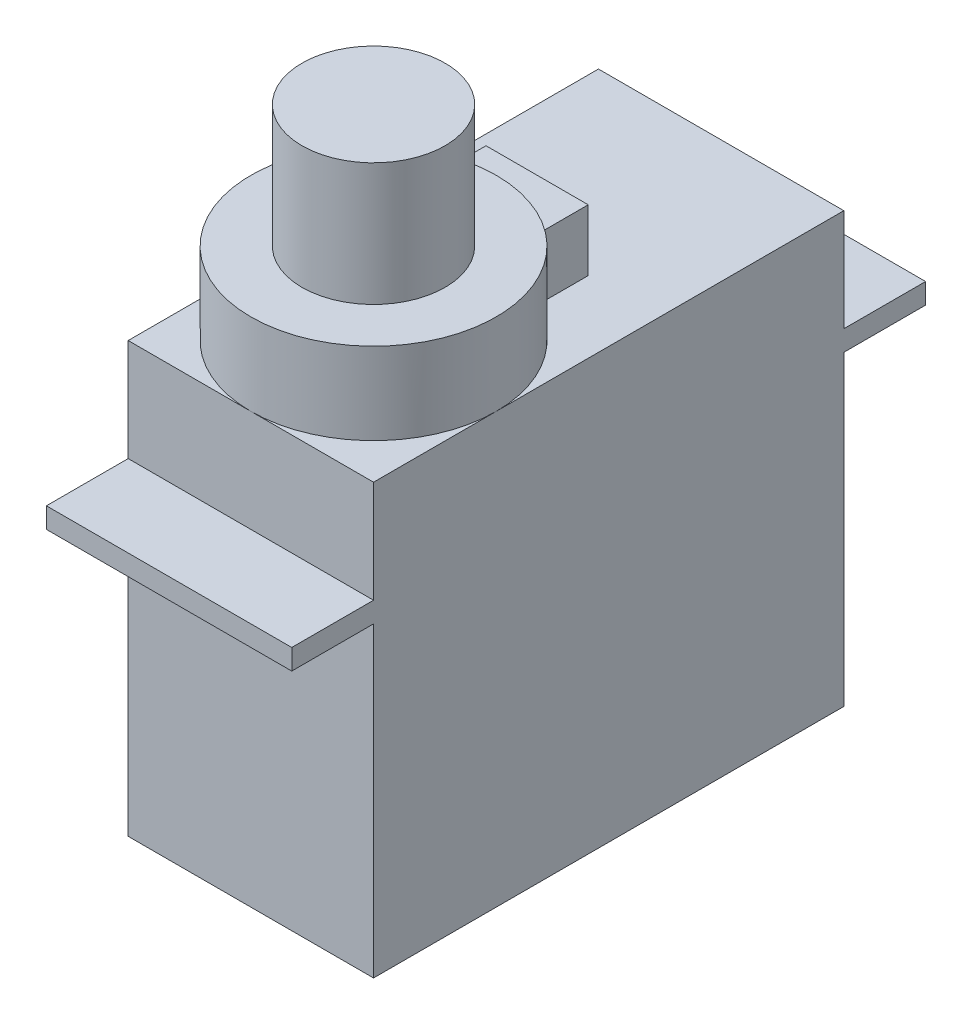
SolidWorks part; units mm, degrees
ref_plane "Front Plane" through (0, 0, 0) normal (0, 0, 1) x (1, 0, 0)
ref_plane "Top Plane" through (0, 0, 0) normal (0, 1, 0) x (1, 0, 0)
ref_plane "Right Plane" through (0, 0, 0) normal (1, 0, 0) x (0, 0, -1)
sketch "Sketch1" plane through (0, 0, 0) normal (0, 1, 0) x (1, 0, 0)
  line L1 (-6, -11.5) -> (6, -11.5)
  line L2 (-6, -11.5) -> (-6, 11.5)
  line L3 (-6, 11.5) -> (6, 11.5)
  line L4 (6, -11.5) -> (6, 11.5)
  line L5 (-6, -11.5) -> (6, 11.5) construction
  line L6 (-6, 11.5) -> (6, -11.5) construction
  point P0 (0, 0)
  dimension "D1" = 12
  dimension "D2" = 23
extrude "Boss-Extrude1" add sketch "Sketch1" along normal blind 21
sketch "Sketch2" plane through (6, 0, 0) normal (1, 0, 0) x (0, 0, -1)
  line L0 (-11.5, 0) -> (11.5, 0) construction
  line L1 (-15.5, 16) -> (15.5, 16)
  line L2 (-15.5, 16) -> (-15.5, 15)
  line L3 (-15.5, 15) -> (15.5, 15)
  line L4 (15.5, 16) -> (15.5, 15)
  line L5 (-11.5, 21) -> (-11.5, 0) construction
  line L6 (0, 0) -> (0, 25.16) construction
  point P11 (0, 16)
  dimension "D1" = 15
  dimension "D2" = 1
  dimension "D3" = 4
extrude "Boss-Extrude2" add sketch "Sketch2" against normal up to surface (12 mm away) up to face at (-6, 10.5, 0)
sketch "Sketch3" plane through (0, 21, 0) normal (0, 1, 0) x (1, 0, 0)
  line L0 (6, -11.5) -> (6, 11.5) construction
  line L1 (-6, 11.5) -> (-6, -11.5) construction
  line L2 (-6, -11.5) -> (6, -11.5) construction
  circle A0 centre (0, -5.5) radius 6
extrude "Boss-Extrude3" add sketch "Sketch3" along normal blind 4
sketch "Sketch4" plane through (0, 21, 0) normal (0, 1, 0) x (1, 0, 0)
  line L0 (0, 0.5) -> (0, -5.5) construction
  line L1 (-2.5, 2.5) -> (2.5, 2.5)
  line L2 (-2.5, 2.5) -> (-2.5, -5.5)
  line L3 (-2.5, -5.5) -> (2.5, -5.5)
  line L4 (2.5, 2.5) -> (2.5, -5.5)
  line L5 (-2.5, 2.5) -> (2.5, -5.5) construction
  line L6 (-2.5, -5.5) -> (2.5, 2.5) construction
  arc A0 (6, -5.5) -> (-6, -5.5) centre (0, -5.5) ccw construction
  point P0 (0, -1.5)
  dimension "D1" = 2
  dimension "D2" = 5
extrude "Boss-Extrude4" add sketch "Sketch4" along normal offset from surface (3 mm away) 1 up to face at (0, 25, 11.5)
sketch "Sketch5" plane through (0, 25, 0) normal (0, 1, 0) x (1, 0, 0)
  circle A0 centre (0, -5.5) radius 3.5
  circle A1 centre (0, -5.5) radius 6
  circle A2 centre (0, -5.5) radius 6 construction
  dimension "D2" = 7
  dimension "D1" = 0
extrude "Boss-Extrude5" add sketch "Sketch5" along normal blind 6
